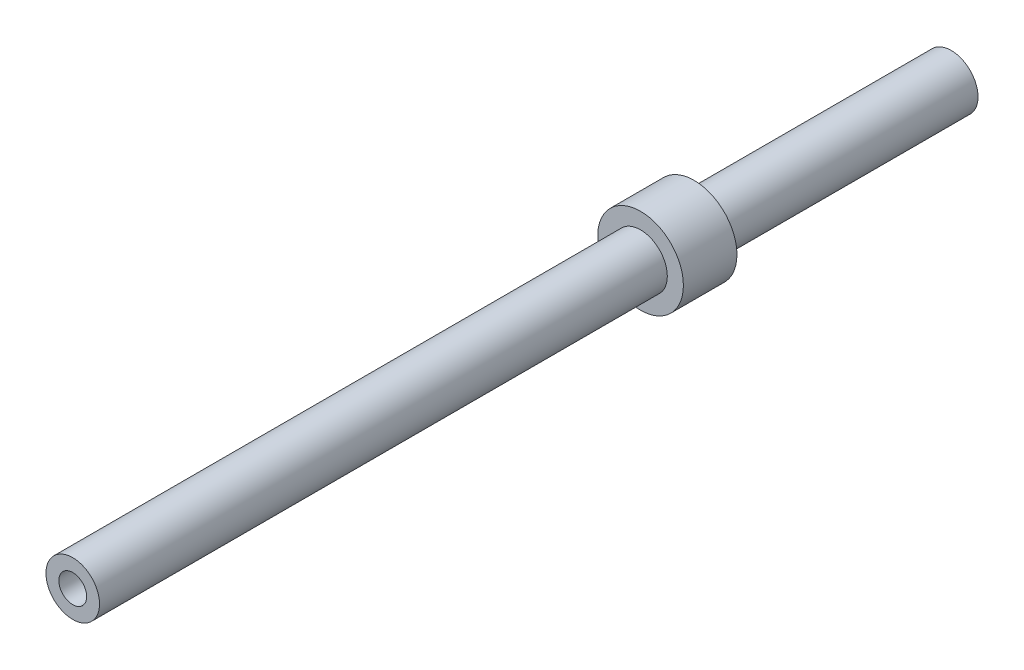
SolidWorks part; units mm, degrees
ref_plane "Front Plane" through (0, 0, 0) normal (0, 0, 1) x (1, 0, 0)
ref_plane "Top Plane" through (0, 0, 0) normal (0, 1, 0) x (1, 0, 0)
ref_plane "Right Plane" through (0, 0, 0) normal (1, 0, 0) x (0, 0, -1)
sketch "Sketch1" plane through (0, 0, 0) normal (0, 0, 1) x (1, 0, 0)
  circle A0 centre (0, 0) radius 2.5
extrude "Boss-Extrude1" add sketch "Sketch1" along normal blind 24
sketch "Sketch2" plane through (0, 0, 24) normal (0, 0, 1) x (1, 0, 0)
  circle A0 centre (0, 0) radius 4
extrude "Boss-Extrude2" add sketch "Sketch2" along normal blind 5
sketch "Sketch3" plane through (0, 0, 29) normal (0, 0, 1) x (1, 0, 0)
  circle A0 centre (0, 0) radius 2.5
extrude "Boss-Extrude3" add sketch "Sketch3" along normal blind 53
sketch "Sketch4" plane through (0, 0, 82) normal (0, 0, 1) x (1, 0, 0)
  point P0 (0, 0)
hole_wizard "M3x0.5 Tapped Hole1" positions "Sketch4" profile "Sketch5" tap size "M3x0.5" standard "JIS"
sketch "Sketch5" plane through (0, 0, 82) normal (1, 0, 0) x (0, -1, 0)
  line L0 (0, 0) -> (0, 8.7811)
  line L1 (0, 8.7811) -> (1.3, 8)
  line L2 (1.3, 8) -> (1.3, 0)
  line L5 (1.3, 0) -> (0, 0)
  line L10 (0, 8.7811) -> (-1.3, 8) construction
  line L11 (0, -6.35) -> (0, 107.95) construction
  dimension "Tap Drill Dia." = 2.6
  dimension "Tap Drill Depth" = 8
  dimension "Drill Angle" = 118
cosmetic thread "Hole Thread1" parameters "D1"=5, "D2"=3
hole_wizard "M3x0.5 Tapped Hole2" positions "Sketch7" profile "Sketch6" tap size "M3x0.5" standard "JIS"
sketch "Sketch7" plane through (0, 0, 0) normal (0, 0, -1) x (-1, 0, 0)
  point P0 (0, 0)
sketch "Sketch6" plane through (0, 0, 0) normal (1, 0, 0) x (0, 1, 0)
  line L0 (0, 0) -> (0, 8.7811)
  line L1 (0, 8.7811) -> (1.3, 8)
  line L2 (1.3, 8) -> (1.3, 0)
  line L5 (1.3, 0) -> (0, 0)
  line L10 (0, 8.7811) -> (-1.3, 8) construction
  line L11 (0, -6.35) -> (0, 107.95) construction
  dimension "Tap Drill Dia." = 2.6
  dimension "Tap Drill Depth" = 8
  dimension "Drill Angle" = 118
cosmetic thread "Hole Thread2" parameters "D1"=5, "D2"=3
